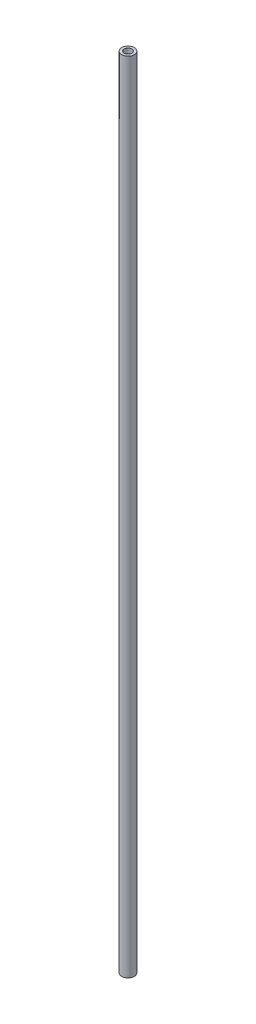
SolidWorks part; units mm, degrees
material "Thornel VCB-20 Carbon Cloth"
ref_plane "Front Plane" through (0, 0, 0) normal (0, 0, 1) x (1, 0, 0)
ref_plane "Top Plane" through (0, 0, 0) normal (0, 1, 0) x (1, 0, 0)
ref_plane "Right Plane" through (0, 0, 0) normal (1, 0, 0) x (0, 0, -1)
sketch "Sketch1" plane through (0, 0, 0) normal (0, 1, 0) x (1, 0, 0)
  circle A0 centre (0, 0) radius 1.5
  circle A1 centre (0, 0) radius 2.5
  dimension "D1" = 3
  dimension "D2" = 5
extrude "Boss-Extrude1" add sketch "Sketch1" along normal blind 318.4
